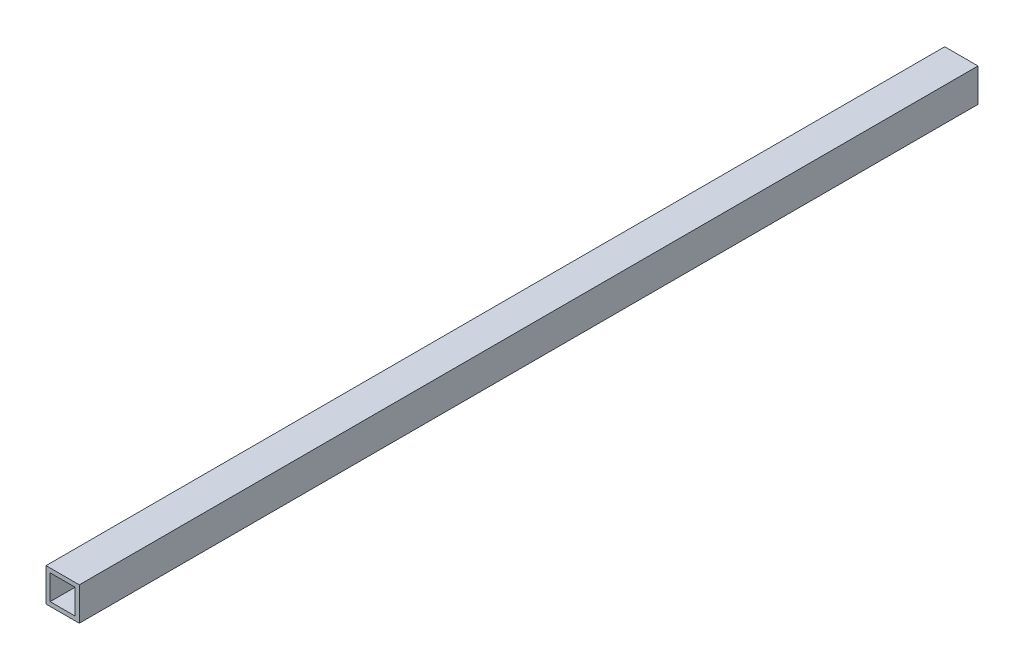
SolidWorks part; units mm, degrees
ref_plane "Front Plane" through (0, 0, 0) normal (0, 0, 1) x (1, 0, 0)
ref_plane "Top Plane" through (0, 0, 0) normal (0, 1, 0) x (1, 0, 0)
ref_plane "Right Plane" through (0, 0, 0) normal (1, 0, 0) x (0, 0, -1)
sketch "Sketch1" plane through (0, 0, 0) normal (0, 0, 1) x (1, 0, 0)
  line L0 (-6.4742, 11.5232) -> (12.5758, 11.5232)
  line L1 (-9.6492, 14.6982) -> (15.7508, 14.6982)
  line L2 (-9.6492, 14.6982) -> (-9.6492, -10.7018)
  line L3 (-9.6492, -10.7018) -> (15.7508, -10.7018)
  line L4 (15.7508, 14.6982) -> (15.7508, -10.7018)
  line L5 (12.5758, 11.5232) -> (12.5758, -7.5268)
  line L6 (-6.4742, -7.5268) -> (12.5758, -7.5268)
  line L7 (-6.4742, 11.5232) -> (-6.4742, -7.5268)
  dimension "D1" = 25.4
  dimension "D2" = 25.4
  dimension "D3" = 3.175
extrude "Boss-Extrude1" add sketch "Sketch1" along normal blind 685.8
